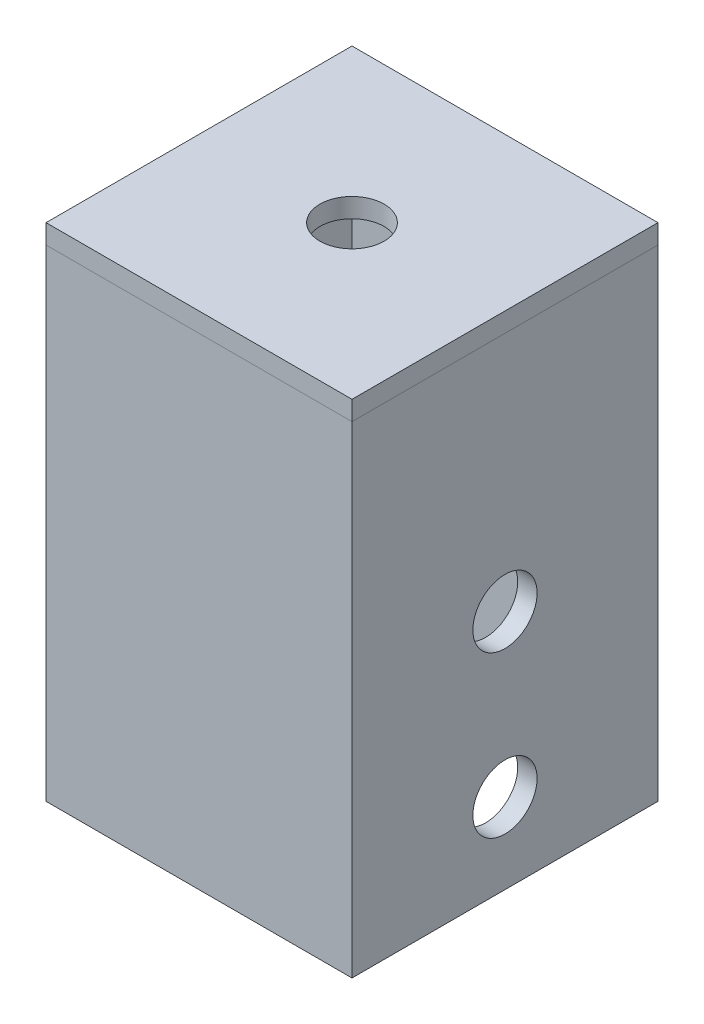
SolidWorks part; units mm, degrees
material "AISI 1020"
ref_plane "Alzado" through (0, 0, 0) normal (0, 0, 1) x (1, 0, 0)
ref_plane "Planta" through (0, 0, 0) normal (0, 1, 0) x (1, 0, 0)
ref_plane "Vista lateral" through (0, 0, 0) normal (1, 0, 0) x (0, 0, -1)
sketch "Croquis1" plane through (0, 0, 0) normal (0, 0, 1) x (1, 0, 0)
  line L0 (0, 0) -> (0, 60)
  dimension "D1" = 60
other "Tubo cuadrado al AL TUBE 1.5 SQR X 0.095 WALL(1)"
ref_plane "Plano1" through (0, 0, 0) normal (0, 1, 0) x (-1, 0, 0)
sketch "Sketch1" plane through (0, 0, 0) normal (0, 1, 0) x (-1, 0, 0)
  line L0 (-16.637, -16.637) -> (-16.637, 16.637)
  line L1 (16.637, 16.637) -> (-16.637, 16.637)
  line L2 (16.637, 16.637) -> (16.637, -16.637)
  line L3 (-16.637, -16.637) -> (16.637, -16.637)
  line L4 (-19.05, -19.05) -> (19.05, -19.05)
  line L5 (-19.05, -19.05) -> (-19.05, 19.05)
  line L6 (19.05, 19.05) -> (-19.05, 19.05)
  line L7 (19.05, 19.05) -> (19.05, -19.05)
  line L8 (0, -16.637) -> (0, -19.05) construction
  line L9 (0, -16.637) -> (0, 16.637) construction
  line L10 (0, 16.637) -> (0, 19.05) construction
  line L11 (19.05, 0) -> (16.637, 0) construction
  line L12 (16.637, 0) -> (-16.637, 0) construction
  line L13 (-16.637, 0) -> (-19.05, 0) construction
  point P14 (0, 0)
  point P17 (0, 0)
  dimension "Thickness" = 2.413
  dimension "V_leg" = 38.1
  dimension "H_leg" = 38.1
sketch "Croquis3" plane through (19.05, 0, 0) normal (1, 0, 0) x (0, 0, -1)
  line L0 (0, 0) -> (0, 10) construction
  line L1 (0, 0) -> (0, 60) construction
  line L2 (0, 10) -> (0, 30) construction
  circle A2 centre (0, 10) radius 4
  circle A3 centre (0, 30) radius 4
  dimension "D3" = 8
  dimension "D4" = 8
  dimension "D1" = 10
  dimension "D2" = 20
extrude "Cortar-Extruir1" cut sketch "Croquis3" against normal through all contours A2 | A3
sketch "Croquis4" plane through (0, 60, 0) normal (0, 1, 0) x (1, 0, 0)
  circle A0 centre (0, 0) radius 4 construction
  dimension "D1" = 8
other "Tapa en extremo1" parameters "D1"=2.41, "D2"=3, "D3"=3
sketch "Croquis5" plane through (0, 62.41, 0) normal (0, 1, 0) x (1, 0, 0)
  circle A0 centre (0, 0) radius 4
  dimension "D1" = 8
extrude "Cortar-Extruir2" cut sketch "Croquis5" against normal blind 10
